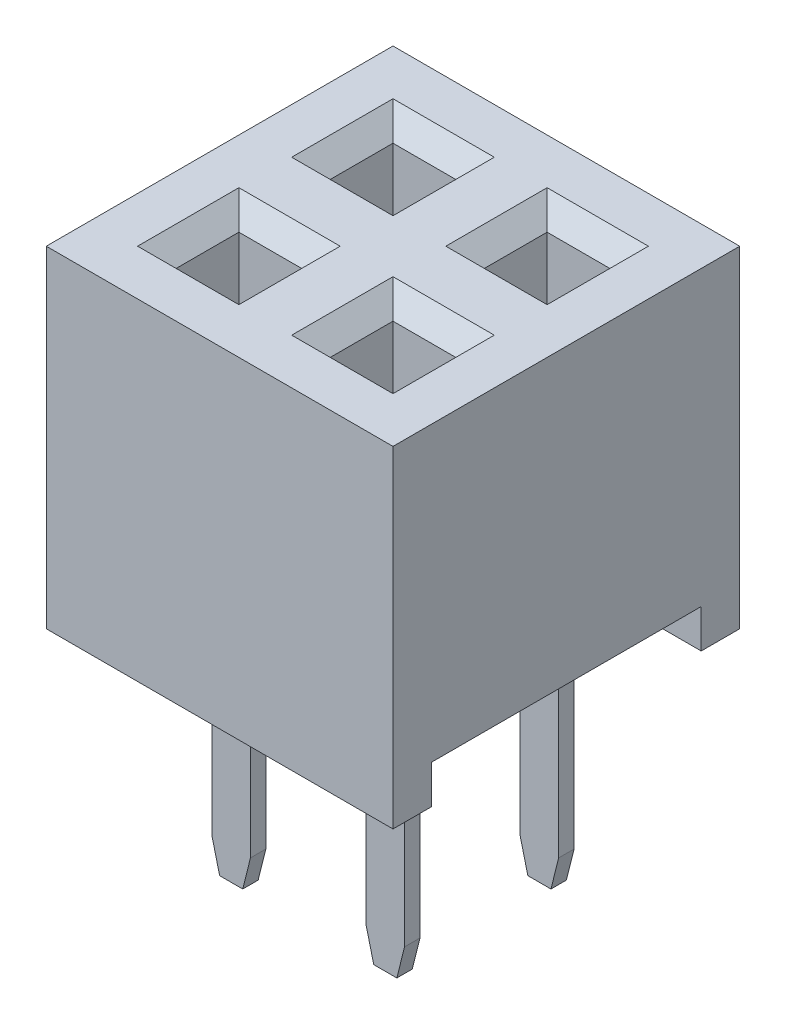
SolidWorks part; units mm, degrees
ref_plane "Front" through (0, 0, 0) normal (0, 0, 1) x (1, 0, 0)
ref_plane "Top" through (0, 0, 0) normal (0, 1, 0) x (1, 0, 0)
ref_plane "Right" through (0, 0, 0) normal (1, 0, 0) x (0, 0, -1)
sketch "草图1" plane through (0, 0, 0) normal (1, 0, 0) x (0, 0, -1)
  line L0 (-2.25, 0) -> (2.25, 0)
  line L1 (2.25, 0) -> (2.25, -4.3)
  line L2 (2.25, -4.3) -> (1.75, -4.3)
  line L3 (1.75, -4.3) -> (1.75, -3.8)
  line L4 (1.75, -3.8) -> (-1.75, -3.8)
  line L5 (0, -3.8) -> (0, 0) construction
  line L6 (-1.75, -4.3) -> (-1.75, -3.8)
  line L7 (-2.25, -4.3) -> (-1.75, -4.3)
  line L8 (-2.25, 0) -> (-2.25, -4.3)
  dimension "D1" = 4.5
  dimension "D2" = 4.3
  dimension "D3" = 0.5
  dimension "D4" = 0.5
extrude "凸台-拉伸1" add sketch "草图1" along normal mid plane 2
sketch "草图3" plane through (0, 0, 0) normal (0, 1, 0) x (1, 0, 0)
  line L0 (0, 2.25) -> (0, -2.25) construction
  line L1 (1, 2.25) -> (-1, 2.25) construction
  line L2 (1, -2.25) -> (-1, -2.25) construction
  line L3 (0, 0) -> (1, 0) construction
  line L4 (0.7333, 0.2667) -> (-0.7333, 0.2667)
  line L5 (0.7333, 0.2667) -> (0.7333, 1.7333)
  line L6 (0.7333, 1.7333) -> (-0.7333, 1.7333)
  line L7 (-0.7333, 0.2667) -> (-0.7333, 1.7333)
  line L8 (1, 0) -> (-0.7333, 1.7333) construction
  line L9 (0.7333, 1.7333) -> (-0.7333, 0.2667) construction
  line L10 (1, 2.25) -> (1, -2.25) construction
  line L12 (0.4074, 0.5926) -> (-0.4074, 0.5926)
  line L13 (0.4074, 0.5926) -> (0.4074, 1.4074)
  line L14 (0.4074, 1.4074) -> (-0.4074, 1.4074)
  line L15 (-0.4074, 0.5926) -> (-0.4074, 1.4074)
  line L16 (0.4074, 0.5926) -> (-0.4074, 1.4074) construction
  line L17 (0.4074, 1.4074) -> (-0.4074, 0.5926) construction
  point P6 (0, 1)
  point P16 (0, 1)
  dimension "D1" = 1
  dimension "D2" = 0.5334
  dimension "D3" = 0.5167
  dimension "D4" = 1.4666
extrude "切除-拉伸1" cut sketch "草图3" against normal blind 3.5 contours L15 L12 L13 L14
chamfer "倒角1" distance 0.25 angle 45 3 edges at (0, 0, -0.5926) (0.4074, 0, -1) (0, 0, -1.4074)
mirror "镜向1" about plane through (0, 0, 0) normal (0, 0, 1) of "倒角1", "切除-拉伸1"
sketch "草图4" plane through (0, 0, 0) normal (1, 0, 0) x (0, 0, -1)
  line L0 (1.563, -3.8) -> (1.1, -4.0888)
  line L1 (-1.75, -3.8) -> (1.75, -3.8) construction
  line L2 (1.1, -4.0888) -> (1.1, -7.1)
  line L3 (1.75, -4.3) -> (2.25, -4.3) construction
  line L4 (1.1851, -3.8) -> (0.9, -3.9778)
  line L5 (0.9, -3.9778) -> (0.9, -7.1)
  line L6 (0.9, -7.1) -> (1.1, -7.1)
  line L7 (1.563, -3.8) -> (1.1851, -3.8)
  line L9 (1.4571, -3.6303) -> (0.9, -3.9778) construction
  point P10 (0, -3.8)
  point P12 (1, -7.1)
  dimension "D1" = 2.8
  dimension "D3" = 1
  dimension "D2" = 0.2
extrude "凸台-拉伸2" add sketch "草图4" along normal blind 0.25
chamfer "倒角2" distance 0.1 distance2 0.4 1 edges at (0.25, -7.1, -1)
sketch "草图5" plane through (0, 0, 0) normal (0, 1, 0) x (1, 0, 0)
  line L0 (1, 2.25) -> (-1, 2.25) construction
  line L1 (0, 2.25) -> (-1, 2.25)
  line L2 (0, 2.25) -> (0, 0)
  line L3 (1, -2.25) -> (-1, -2.25)
  line L4 (-1, 2.25) -> (-1, -2.25)
  line L5 (0, 0) -> (1, 0)
  line L6 (1, 2.25) -> (1, -2.25) construction
  line L7 (1, 0) -> (1, -2.25)
extrude "切除-拉伸2" cut sketch "草图5" against normal through all
mirror "镜向3" about plane through (0, 0, 0) normal (1, 0, 0) of bodies 106
mirror "镜向4" about plane through (0, -7.1, 0) normal (0, 0, -1) of bodies 107
sketch "草图6" plane through (1, 0, 0) normal (1, 0, 0) x (0, 0, -1)
  line L8 (2.25, 0) -> (-2.25, 0)
  line L9 (-2.25, 0) -> (-2.25, -4.3)
  line L10 (-2.25, -4.3) -> (-1.75, -4.3)
  line L11 (-1.75, -4.3) -> (-1.75, -3.8)
  line L12 (-1.75, -3.8) -> (1.75, -3.8)
  line L13 (1.75, -3.8) -> (1.75, -4.3)
  line L14 (1.75, -4.3) -> (2.25, -4.3)
  line L15 (2.25, -4.3) -> (2.25, 0)
  line L16 (2.25, 0) -> (-2.25, 0)
  line L17 (-2.25, 0) -> (-2.25, -4.3)
  line L18 (-2.25, -4.3) -> (-1.75, -4.3)
  line L19 (-1.75, -4.3) -> (-1.75, -3.8)
  line L20 (-1.75, -3.8) -> (1.75, -3.8)
  line L21 (1.75, -3.8) -> (1.75, -4.3)
  line L22 (1.75, -4.3) -> (2.25, -4.3)
  line L23 (2.25, -4.3) -> (2.25, 0)
  dimension "D1" = 0
extrude "凸台-拉伸4" add sketch "草图6" along normal blind 0.25
mirror "镜向5"
ref_plane "基准面1" through (0, 0, 0) normal (0, 0, 1) x (1, 0, 0)
ref_plane "基准面2" through (-1, 0, 0) normal (-1, 0, 0) x (0, 0, 1)
